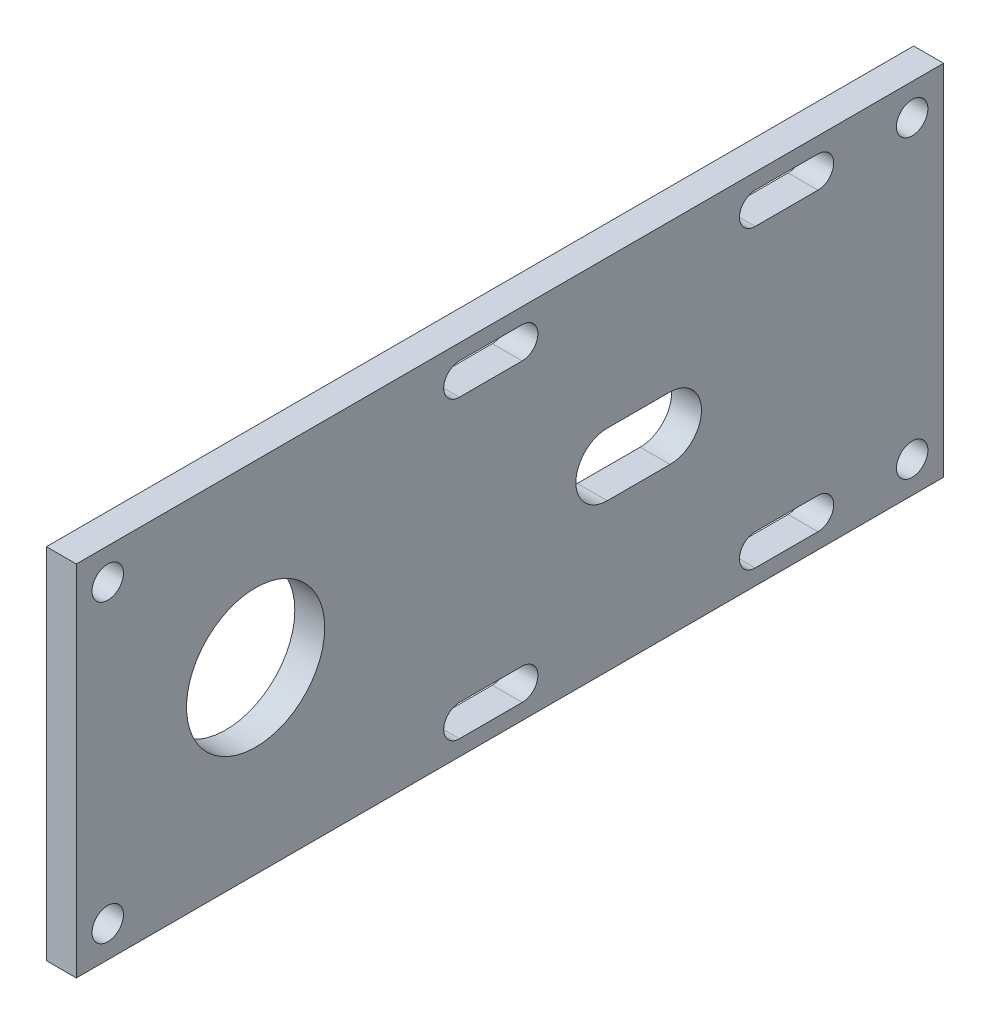
SolidWorks part; units mm, degrees
ref_plane "Front Plane" through (0, 0, 0) normal (0, 0, 1) x (1, 0, 0)
ref_plane "Top Plane" through (0, 0, 0) normal (0, 1, 0) x (1, 0, 0)
ref_plane "Right Plane" through (0, 0, 0) normal (1, 0, 0) x (0, 0, -1)
sketch "Sketch1" plane through (0, 0, 0) normal (-1, 0, 0) x (0, 0, 1)
  line L0 (-52.1, -5) -> (-5, -52.1) construction
  line L1 (-138.1, 0) -> (0, 0)
  line L2 (-138.1, 0) -> (-138.1, -57.1)
  line L3 (-138.1, -57.1) -> (0, -57.1)
  line L4 (0, 0) -> (0, -57.1)
  line L5 (-108.1, -5) -> (-118.1, -5) construction
  line L6 (-71, -52.1) -> (-118.1, -5) construction
  line L7 (-71, -5) -> (-71, -52.1) construction
  line L8 (-118.1, -5) -> (-118.1, -52.1) construction
  line L9 (-133.1, -5) -> (-133.1, -52.1) construction
  line L10 (-133.1, -5) -> (-52.1, -5) construction
  line L11 (-52.1, -5) -> (-5, -5) construction
  line L12 (-52.1, -5) -> (-52.1, -52.1) construction
  line L13 (-52.1, -52.1) -> (-5, -52.1) construction
  line L14 (-5, -5) -> (-5, -52.1) construction
  line L15 (-133.1, -52.1) -> (-52.1, -52.1) construction
  line L16 (-108.1, -7.5) -> (-118.1, -7.5)
  line L17 (-108.1, -2.5) -> (-118.1, -2.5)
  line L18 (-108.1, -52.1) -> (-118.1, -52.1) construction
  line L19 (-108.1, -54.6) -> (-118.1, -54.6)
  line L20 (-108.1, -49.6) -> (-118.1, -49.6)
  line L21 (-61, -5) -> (-71, -5) construction
  line L22 (-61, -7.5) -> (-71, -7.5)
  line L23 (-61, -2.5) -> (-71, -2.5)
  line L24 (-61, -52.1) -> (-71, -52.1) construction
  line L25 (-61, -54.6) -> (-71, -54.6)
  line L26 (-61, -49.6) -> (-71, -49.6)
  line L27 (-84.55, -28.55) -> (-94.55, -28.55) construction
  line L28 (-84.55, -33.55) -> (-94.55, -33.55)
  line L29 (-84.55, -23.55) -> (-94.55, -23.55)
  circle A0 centre (-133.1, -5) radius 2.5
  circle A3 centre (-133.1, -52.1) radius 2.5
  arc A9 (-108.1, -7.5) -> (-108.1, -2.5) centre (-108.1, -5) ccw
  arc A10 (-118.1, -2.5) -> (-118.1, -7.5) centre (-118.1, -5) ccw
  arc A12 (-108.1, -54.6) -> (-108.1, -49.6) centre (-108.1, -52.1) ccw
  circle A15 centre (-28.55, -28.55) radius 11
  arc A16 (-118.1, -49.6) -> (-118.1, -54.6) centre (-118.1, -52.1) ccw
  circle A17 centre (-5, -5) radius 2.5
  circle A18 centre (-5, -52.1) radius 2.5
  arc A21 (-61, -7.5) -> (-61, -2.5) centre (-61, -5) ccw
  arc A22 (-71, -2.5) -> (-71, -7.5) centre (-71, -5) ccw
  arc A23 (-61, -54.6) -> (-61, -49.6) centre (-61, -52.1) ccw
  arc A24 (-71, -49.6) -> (-71, -54.6) centre (-71, -52.1) ccw
  arc A25 (-84.55, -33.55) -> (-84.55, -23.55) centre (-84.55, -28.55) ccw
  arc A26 (-94.55, -23.55) -> (-94.55, -33.55) centre (-94.55, -28.55) ccw
  point P7 (-94.55, -28.55)
  point P37 (-28.55, -28.55)
  point P40 (-113.1, -5)
  point P45 (-113.1, -52.1)
  point P52 (-66, -5)
  point P59 (-66, -52.1)
  point P68 (-89.55, -28.55)
  dimension "D1" = 5
  dimension "D2" = 5
  dimension "D9" = 47.1
  dimension "D10" = 22
  dimension "D4" = 5
  dimension "D6" = 2.5
  dimension "D11" = 47.1
  dimension "D7" = 5
  dimension "D3" = 5
  dimension "D5" = 5
  dimension "D8" = 10
  dimension "D12" = 20
  dimension "D13" = 61
extrude "Boss-Extrude1" add sketch "Sketch1" along normal blind 4.7625
ref_plane "Plane1" through (0, -28.55, 0) normal (0, 1, 0) x (1, 0, 0)
